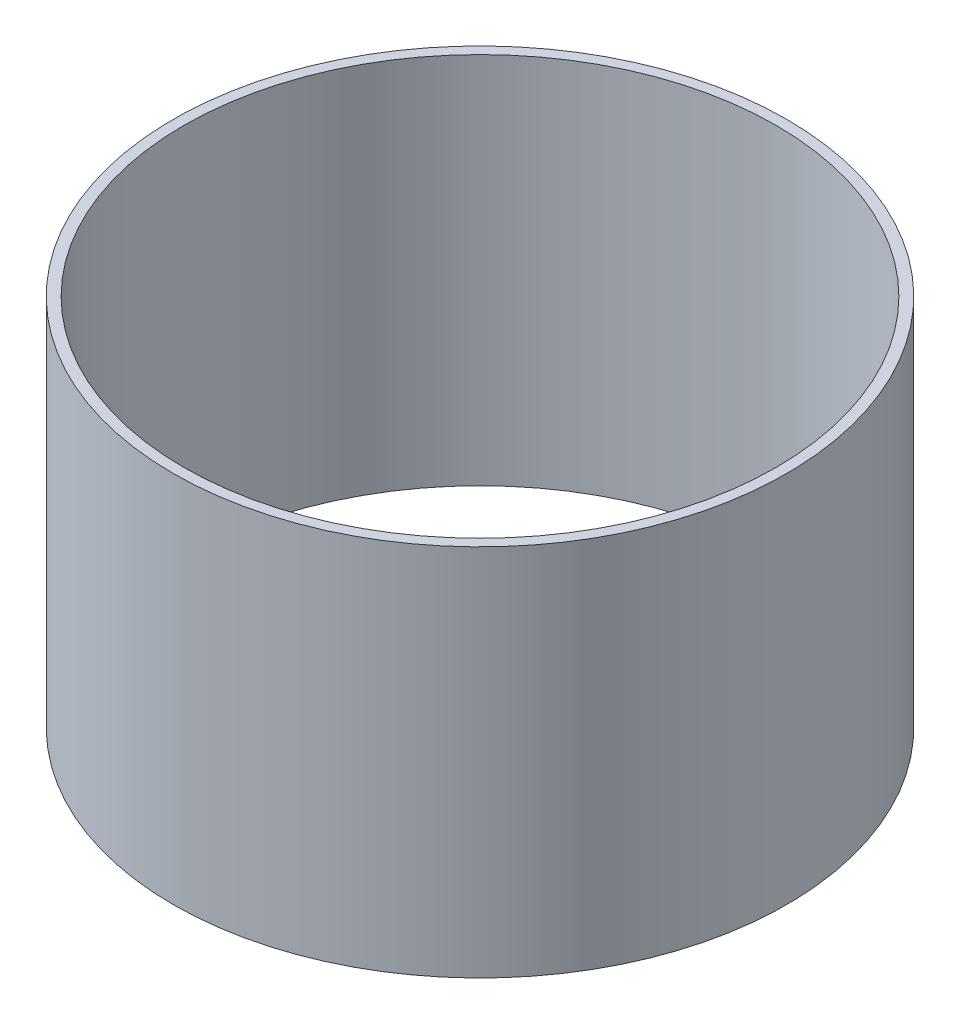
SolidWorks part; units mm, degrees
material "AISI 304"
ref_plane "Front" through (0, 0, 0) normal (0, 0, 1) x (1, 0, 0)
ref_plane "Top" through (0, 0, 0) normal (0, 1, 0) x (1, 0, 0)
ref_plane "Right" through (0, 0, 0) normal (1, 0, 0) x (0, 0, -1)
sketch "Sketch1" plane through (0, 0, 0) normal (0, 1, 0) x (1, 0, 0)
  circle A0 centre (0, 0) radius 109.5375
  circle A1 centre (0, 0) radius 105.7783
  dimension "D1" = 219.075
  dimension "D2" = 3.7592
extrude "Boss-Extrude1" add sketch "Sketch1" along normal mid plane 133.35
